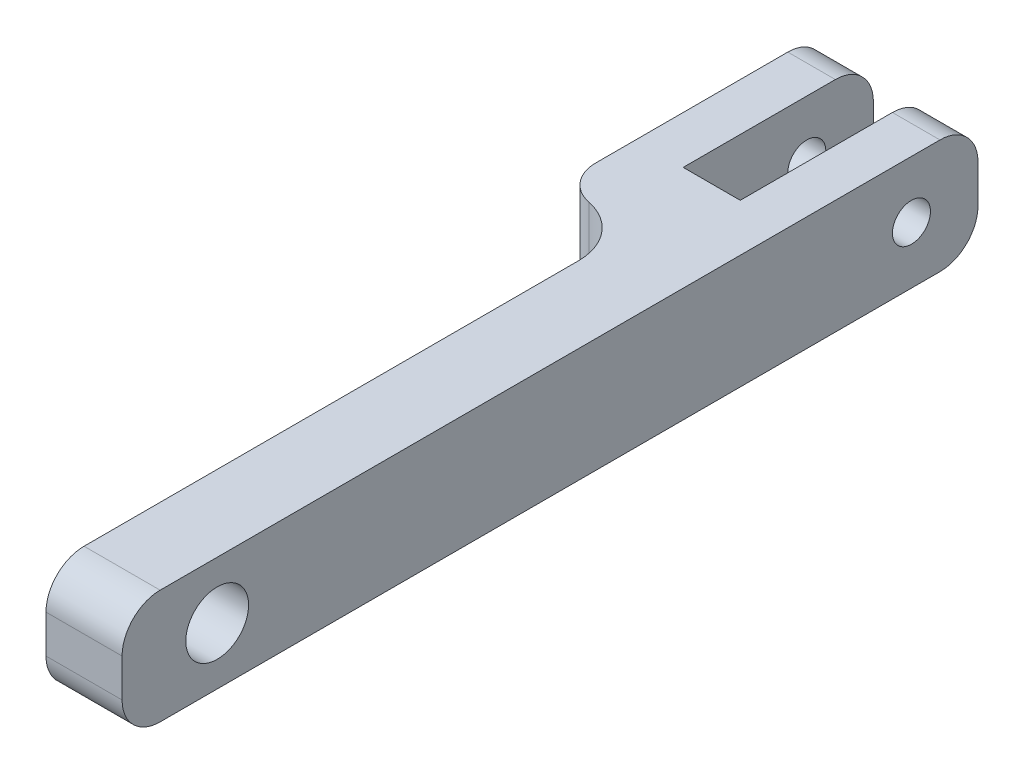
SolidWorks part; units mm, degrees
ref_plane "Front" through (0, 0, 0) normal (0, 0, 1) x (1, 0, 0)
ref_plane "Top" through (0, 0, 0) normal (0, 1, 0) x (1, 0, 0)
ref_plane "Right" through (0, 0, 0) normal (1, 0, 0) x (0, 0, -1)
sketch "Sketch1" plane through (0, 0, 0) normal (1, 0, 0) x (0, 0, -1)
  line L1 (0, 0) -> (45, 0)
  line L2 (0, 0) -> (0, -6)
  line L3 (0, -6) -> (45, -6)
  line L4 (45, 0) -> (45, -6)
  dimension "D1" = 6
  dimension "D2" = 45
extrude "Boss-Extrude1" add sketch "Sketch1" along normal blind 4
sketch "Sketch2" plane through (4, 0, 0) normal (1, 0, 0) x (0, 0, -1)
  line L0 (0, 0) -> (0, -6) construction
  line L2 (0, -6) -> (45, -6) construction
  circle A0 centre (5, -3) radius 1.65
  dimension "D1" = 3.3
  dimension "D3" = 5
  dimension "D2" = 3
extrude "Cut-Extrude1" cut sketch "Sketch2" against normal through all
sketch "Sketch4" plane through (0, 0, 0) normal (-1, 0, 0) x (0, 0, 1)
  line L0 (-45, 0) -> (0, 0) construction
  line L1 (-45, -6) -> (-31, -6)
  line L2 (-45, -6) -> (-45, 0)
  line L3 (-45, 0) -> (-31, 0)
  line L4 (-31, -6) -> (-31, 0)
  dimension "D1" = 14
extrude "Boss-Extrude2" add sketch "Sketch4" along normal blind 4
sketch "Sketch5" plane through (0, 0, -45) normal (0, 0, -1) x (-1, 0, 0)
  line L0 (-4, -6) -> (4, -6) construction
  line L1 (-1.5, -6) -> (1.5, -6)
  line L2 (-1.5, -6) -> (-1.5, 0)
  line L3 (-1.5, 0) -> (1.5, 0)
  line L4 (1.5, -6) -> (1.5, 0)
  line L5 (-4, 0) -> (4, 0) construction
  dimension "D1" = 3
  dimension "D2" = 2.5
extrude "Cut-Extrude2" cut sketch "Sketch5" against normal blind 10
sketch "Sketch6" plane through (-4, 0, 0) normal (-1, 0, 0) x (0, 0, 1)
  line L0 (-45, 0) -> (-45, -6) construction
  line L1 (-45, -6) -> (-31, -6) construction
  circle A0 centre (-41.5, -3) radius 1
  dimension "D1" = 2
  dimension "D2" = 3.5
  dimension "D3" = 3
extrude "Cut-Extrude3" cut sketch "Sketch6" against normal through all
fillet "Fillet1" radius 2 4 edges at (2, 0, 0) (2.75, 0, -45) (2.75, -6, -45) (2, -6, 0)
fillet "Fillet2" radius 3 1 edges at (0, -3, -31)
fillet "Fillet3" radius 2 1 edges at (-4, -3, -31)
fillet "Fillet4" radius 2 2 edges at (-2.75, 0, -45) (-2.75, -6, -45)
equation "\"D3@Sketch6\"=\"D1@Sketch1\"/2"
equation "\"D2@Sketch2\"=\"D1@Sketch1\"/2"
